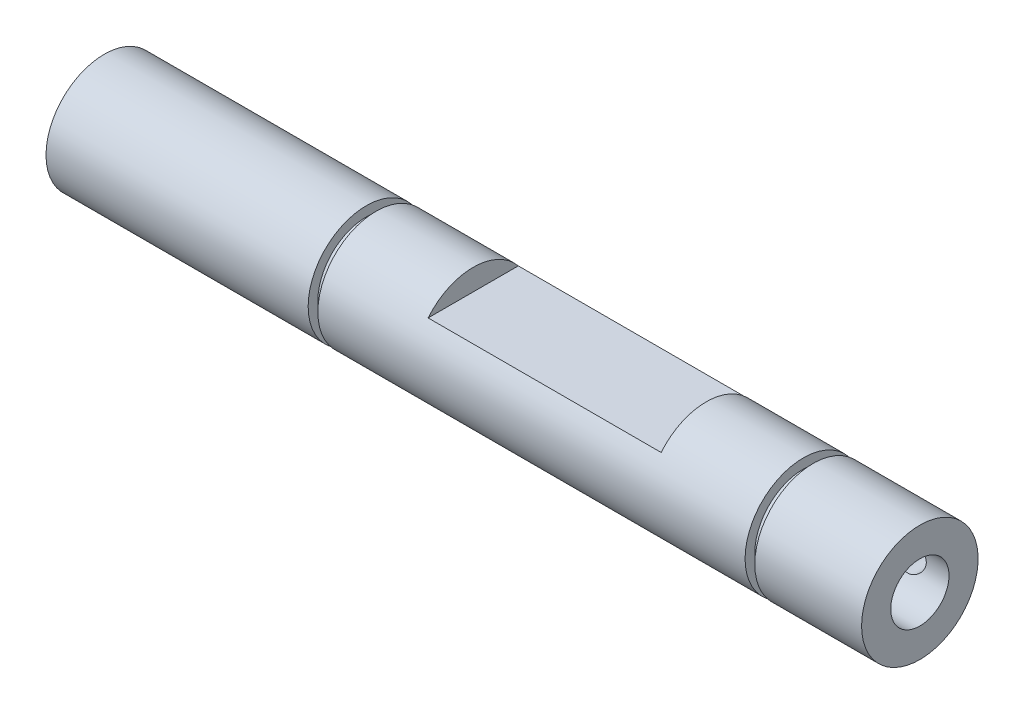
SolidWorks part; units mm, degrees
material "Plain Carbon Steel"
ref_plane "Front Plane" through (0, 0, 0) normal (0, 0, 1) x (1, 0, 0)
ref_plane "Top Plane" through (0, 0, 0) normal (0, 1, 0) x (1, 0, 0)
ref_plane "Right Plane" through (0, 0, 0) normal (1, 0, 0) x (0, 0, -1)
sketch "Sketch1" plane through (0, 0, 0) normal (0, 0, 1) x (1, 0, 0)
  line L0 (55, 0) -> (-55, 0) construction
  line L1 (-45.9334, 0) -> (38.0666, 0)
  line L2 (-45.9334, 0) -> (-45.9334, 6)
  line L3 (-45.9334, 6) -> (-18.9334, 6)
  line L4 (38.0666, 0) -> (38.0666, 6)
  line L5 (27.0666, 6) -> (38.0666, 6)
  line L7 (27.0666, 6) -> (27.0666, 5)
  line L8 (27.0666, 5) -> (26.0666, 5)
  line L9 (26.0666, 6) -> (26.0666, 5)
  line L10 (-17.9334, 6) -> (26.0666, 6)
  line L12 (-17.9334, 6) -> (-17.9334, 5)
  line L13 (-17.9334, 5) -> (-18.9334, 5)
  line L14 (-18.9334, 6) -> (-18.9334, 5)
  point P14 (-17.9334, 5.5)
  dimension "D1" = 84
  dimension "D2" = 6
  dimension "D3" = 1
  dimension "D4" = 5
  dimension "D5" = 11
  dimension "D6" = 44
revolve "Revolve1" add sketch "Sketch1" angle 360 about L1
sketch "Sketch2" plane through (38.0666, 0, 0) normal (1, 0, 0) x (0, 0, -1)
  circle A1 centre (0, 0) radius 3
extrude "Cut-Extrude1" cut sketch "Sketch2" against normal blind 10
sketch "Sketch3" plane through (0, 0, 0) normal (0, 0, 1) x (1, 0, 0)
  line L0 (55, 0) -> (-55, 0) construction
  circle A0 centre (34.2311, 0) radius 1.5
extrude "Cut-Extrude2" cut sketch "Sketch3" against normal blind 10
cosmetic thread "Cosmetic Thread1" parameters "D1"=3.4019, "D2"=4
ref_plane "Plane1" through (0, 6, 0) normal (0, 1, 0) x (1, 0, 0)
sketch "Sketch5" plane through (0, 6, 0) normal (0, 1, 0) x (1, 0, 0)
  line L6 (-5.9334, 0) -> (14.0666, 0) construction
  line L7 (-44.2539, 0) -> (44.2539, 0) construction
  line L8 (-5.9334, 2) -> (14.0666, 2)
  line L9 (-5.9334, -2) -> (14.0666, -2)
  line L10 (27.0666, 6) -> (27.0666, -6) construction
  arc A1 (-5.9334, 2) -> (-5.9334, -2) centre (-5.9334, 0) ccw
  arc A2 (14.0666, -2) -> (14.0666, 2) centre (14.0666, 0) ccw
  point P4 (4.0666, 0)
  dimension "D1" = 2
  dimension "D2" = 13
  dimension "D3" = 20
extrude "Cut-Extrude3" cut sketch "Sketch5" against normal blind 2.2
sketch "Sketch6" plane through (0, 0, 0) normal (0, 0, 1) x (1, 0, 0)
  line L0 (14.0666, 5.6569) -> (-5.9334, 5.6569) construction
  line L1 (-7.9334, 3.8) -> (16.0666, 3.8)
  line L2 (-7.9334, 3.8) -> (-7.9334, 7.5137)
  line L3 (-7.9334, 7.5137) -> (16.0666, 7.5137)
  line L4 (16.0666, 3.8) -> (16.0666, 7.5137)
  line L5 (-7.9334, 3.8) -> (16.0666, 7.5137) construction
  line L6 (-7.9334, 7.5137) -> (16.0666, 3.8) construction
  line L7 (14.0666, 3.8) -> (-5.9334, 3.8) construction
  point P0 (4.0666, 5.6569)
  dimension "D1" = 24
extrude "Cut-Extrude4" cut sketch "Sketch6" against normal mid plane 16
